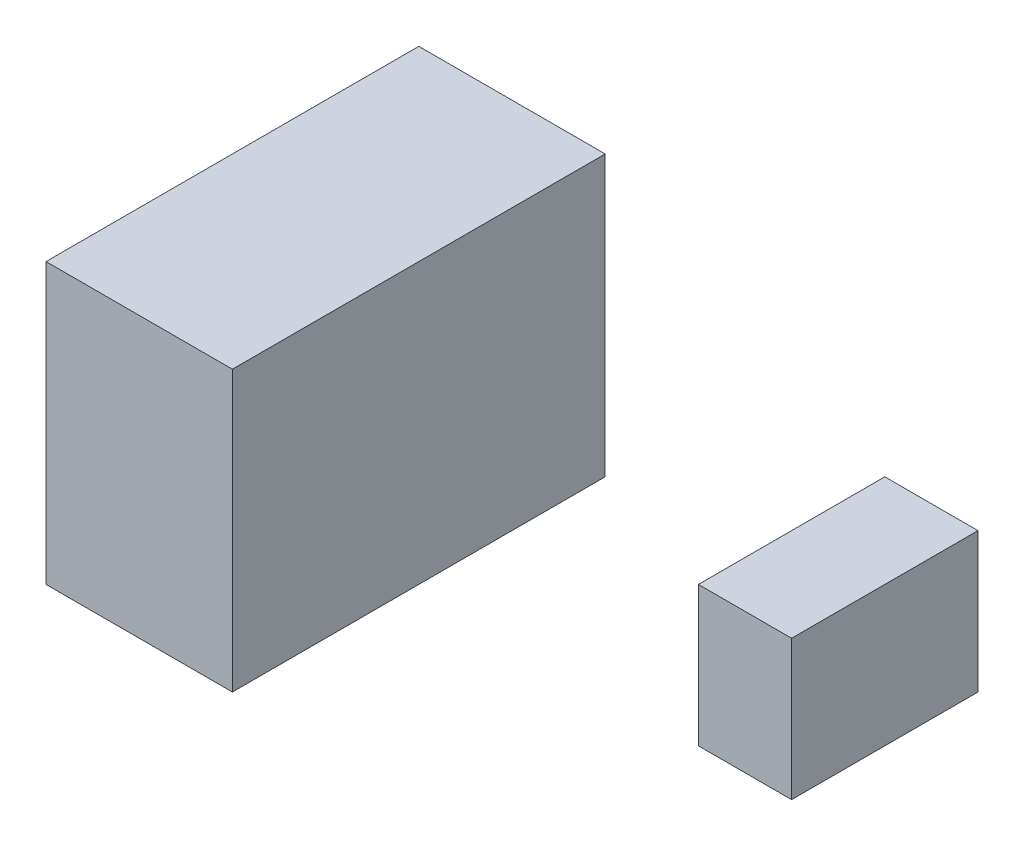
SolidWorks part; units mm, degrees
ref_plane "Front Plane" through (0, 0, 0) normal (0, 0, 1) x (1, 0, 0)
ref_plane "Top Plane" through (0, 0, 0) normal (0, 1, 0) x (1, 0, 0)
ref_plane "Right Plane" through (0, 0, 0) normal (1, 0, 0) x (0, 0, -1)
ref_plane "plane:base-xy" through (0, 0, 0) normal (0, 0, 1) x (1, 0, 0)
sketch "sketch:large" plane through (0, 0, 0) normal (0, 0, 1) x (1, 0, 0)
  line L0 (0, 0) -> (20, 0)
  line L1 (20, 0) -> (20, 30)
  line L2 (20, 30) -> (0, 30)
  line L3 (0, 30) -> (0, 0)
extrude "feature:large" add sketch "sketch:large" along normal blind 40 separate body
sketch "sketch:small" plane through (0, 0, 0) normal (0, 0, 1) x (1, 0, 0)
  line L0 (50, 0) -> (60, 0)
  line L1 (60, 0) -> (60, 15)
  line L2 (60, 15) -> (50, 15)
  line L3 (50, 15) -> (50, 0)
extrude "feature:small" add sketch "sketch:small" along normal blind 20 separate body
